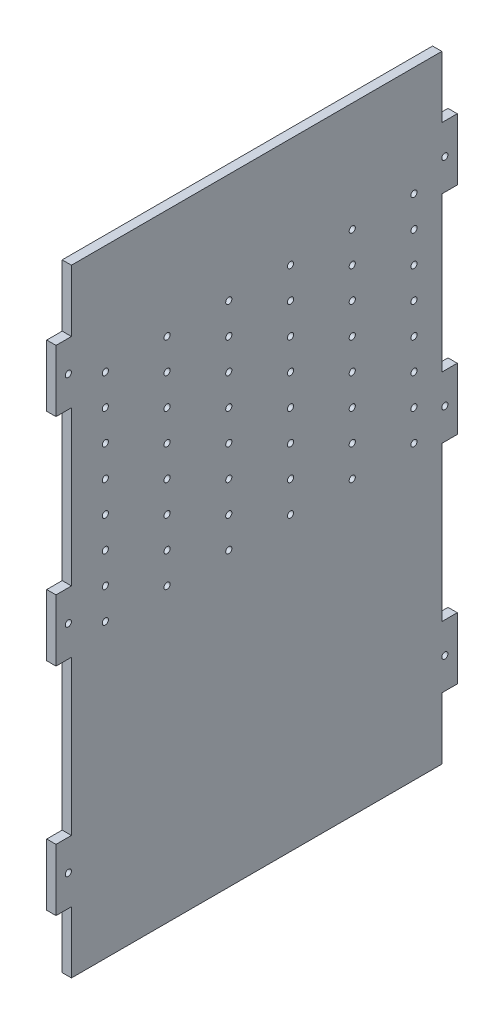
SolidWorks part; units mm, degrees
ref_plane "Front Plane" through (0, 0, 0) normal (1, 0, 0) x (0, 1, 0)
ref_plane "Top Plane" through (0, 0, 0) normal (0, 0, 1) x (0, 1, 0)
ref_plane "Right Plane" through (0, 0, 0) normal (0, 1, 0) x (-1, 0, 0)
sketch "Sketch1" plane through (0, 0, 0) normal (1, 0, 0) x (0, 1, 0)
  line L0 (-80, 60) -> (-80, 65)
  line L1 (-100, 60) -> (-80, 60)
  line L2 (-100, 60) -> (-100, -60)
  line L3 (-100, -60) -> (-80, -60)
  line L4 (100, 60) -> (100, -60)
  line L5 (-80, 65) -> (-60, 65)
  line L6 (-60, 65) -> (-60, 60)
  line L7 (0, 99.2979) -> (0, -106.0143) construction
  line L8 (232.3568, 0) -> (-207.1848, 0) construction
  line L9 (-10, 60) -> (-10, 65)
  line L10 (-10, 65) -> (10, 65)
  line L11 (10, 65) -> (10, 60)
  line L12 (80, 60) -> (80, 65)
  line L13 (80, 65) -> (60, 65)
  line L14 (60, 65) -> (60, 60)
  line L15 (80, -60) -> (80, -65)
  line L16 (80, -65) -> (60, -65)
  line L17 (60, -65) -> (60, -60)
  line L18 (10, -65) -> (10, -60)
  line L19 (-10, -65) -> (10, -65)
  line L20 (-10, -60) -> (-10, -65)
  line L21 (-80, -60) -> (-80, -65)
  line L22 (-80, -65) -> (-60, -65)
  line L23 (-60, -65) -> (-60, -60)
  line L24 (80, 60) -> (100, 60)
  line L25 (10, 60) -> (60, 60)
  line L26 (-60, 60) -> (-10, 60)
  line L27 (-60, -60) -> (-10, -60)
  line L28 (10, -60) -> (60, -60)
  line L29 (80, -60) -> (100, -60)
  line L30 (-13.4302, 49.0187) -> (71.2012, 49.0187) construction
  line L31 (-13.4302, 56.4065) -> (71.2012, 56.4065)
  line L32 (-13.4302, 56.4065) -> (-13.4302, -54.4487)
  line L33 (-13.4302, -54.4487) -> (71.2012, -54.4487)
  line L34 (71.2012, 56.4065) -> (71.2012, -54.4487)
  circle A0 centre (-5.4459, 49.0187) radius 1
  circle A1 centre (4.5541, 49.0187) radius 1
  circle A2 centre (14.5541, 49.0187) radius 1
  circle A3 centre (24.5541, 49.0187) radius 1
  circle A4 centre (34.5541, 49.0187) radius 1
  circle A5 centre (44.5541, 49.0187) radius 1
  circle A6 centre (54.5541, 49.0187) radius 1
  circle A7 centre (64.5541, 49.0187) radius 1
  circle A8 centre (-5.4459, 29.0187) radius 1
  circle A9 centre (4.5541, 29.0187) radius 1
  circle A10 centre (14.5541, 29.0187) radius 1
  circle A11 centre (24.5541, 29.0187) radius 1
  circle A12 centre (34.5541, 29.0187) radius 1
  circle A13 centre (44.5541, 29.0187) radius 1
  circle A14 centre (54.5541, 29.0187) radius 1
  circle A15 centre (64.5541, 29.0187) radius 1
  circle A16 centre (-5.4459, 9.0187) radius 1
  circle A17 centre (4.5541, 9.0187) radius 1
  circle A18 centre (14.5541, 9.0187) radius 1
  circle A19 centre (24.5541, 9.0187) radius 1
  circle A20 centre (34.5541, 9.0187) radius 1
  circle A21 centre (44.5541, 9.0187) radius 1
  circle A22 centre (54.5541, 9.0187) radius 1
  circle A23 centre (64.5541, 9.0187) radius 1
  circle A24 centre (-5.4459, -10.9813) radius 1
  circle A25 centre (4.5541, -10.9813) radius 1
  circle A26 centre (14.5541, -10.9813) radius 1
  circle A27 centre (24.5541, -10.9813) radius 1
  circle A28 centre (34.5541, -10.9813) radius 1
  circle A29 centre (44.5541, -10.9813) radius 1
  circle A30 centre (54.5541, -10.9813) radius 1
  circle A31 centre (64.5541, -10.9813) radius 1
  circle A32 centre (-5.4459, -30.9813) radius 1
  circle A33 centre (4.5541, -30.9813) radius 1
  circle A34 centre (14.5541, -30.9813) radius 1
  circle A35 centre (24.5541, -30.9813) radius 1
  circle A36 centre (34.5541, -30.9813) radius 1
  circle A37 centre (44.5541, -30.9813) radius 1
  circle A38 centre (54.5541, -30.9813) radius 1
  circle A39 centre (64.5541, -30.9813) radius 1
  circle A40 centre (-5.4459, -50.9813) radius 1
  circle A41 centre (4.5541, -50.9813) radius 1
  circle A42 centre (14.5541, -50.9813) radius 1
  circle A43 centre (24.5541, -50.9813) radius 1
  circle A44 centre (34.5541, -50.9813) radius 1
  circle A45 centre (44.5541, -50.9813) radius 1
  circle A46 centre (54.5541, -50.9813) radius 1
  circle A47 centre (64.5541, -50.9813) radius 1
  circle A48 centre (-70, 61) radius 1
  circle A49 centre (70, 61) radius 1
  circle A50 centre (0, 61) radius 1
  circle A51 centre (70, -61) radius 1
  circle A52 centre (0, -61) radius 1
  circle A53 centre (-70, -61) radius 1
  point P6 (-100, 0)
  point P17 (0, 65)
  dimension "D8" = 2
  dimension "D10" = 6
  dimension "D11" = 2
  dimension "D13" = 2
  dimension "D1" = 200
  dimension "D2" = 120
  dimension "D3" = 20
  dimension "D4" = 5
  dimension "D5" = 20
  dimension "D6" = 20
  dimension "D7" = 5
  dimension "D12" = 4
  dimension "D9" = 8
extrude "Boss-Extrude1" add sketch "Sketch1" along normal blind 3 contours L15 L29 L4 L24 L12 L13 L14 L25 L11 L10 L9 L26 L6 L5 L0 L1 L2 L3 L21 L22 L23 L27 L20 L19 L18 L28 L17 L16 L31 L34 L33 L32 | L34 L31 L32 L33 A47 A46 A45 A44 A43 A42 A41 A40 A39 A38 A37 A36 A35 A34 A33 A32 A31 A30 A29 A28 A27 A26 A25
